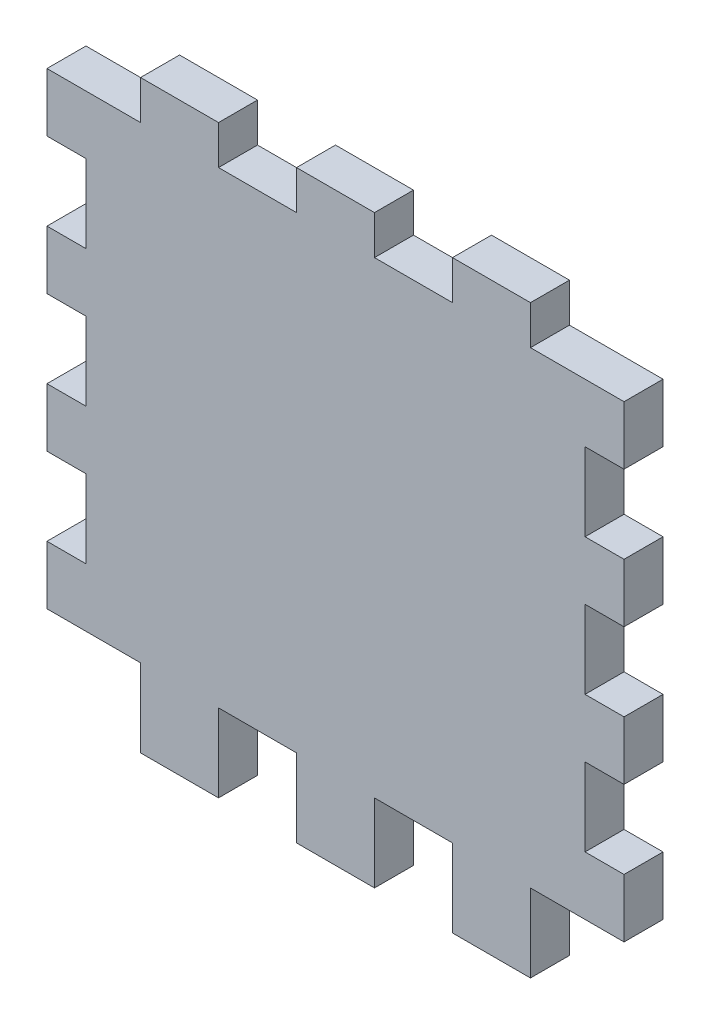
SolidWorks part; units mm, degrees
material "Beech"
ref_plane "Front" through (0, 0, 0) normal (0, 0, 1) x (1, 0, 0)
ref_plane "Top" through (0, 0, 0) normal (0, 1, 0) x (1, 0, 0)
ref_plane "Right" through (0, 0, 0) normal (1, 0, 0) x (0, 0, -1)
sketch "Sketch1" plane through (0, 0, 0) normal (0, 0, 1) x (1, 0, 0)
  line L0 (-2.5, -15) -> (-2.5, -20)
  line L1 (-18.5, -15) -> (18.5, -15)
  line L2 (-18.5, -15) -> (-18.5, 15) construction
  line L3 (-18.5, 15) -> (18.5, 15)
  line L4 (18.5, -15) -> (18.5, 15) construction
  line L5 (-18.5, -15) -> (18.5, 15) construction
  line L6 (-18.5, 15) -> (18.5, -15) construction
  line L7 (7.5, 15) -> (12.5, 15)
  line L8 (7.5, 15) -> (7.5, 17.5)
  line L9 (7.5, 17.5) -> (12.5, 17.5)
  line L10 (12.5, 15) -> (12.5, 17.5)
  line L11 (7.5, 15) -> (12.5, 17.5) construction
  line L12 (7.5, 17.5) -> (12.5, 15) construction
  line L13 (7.5, -15) -> (12.5, -15)
  line L14 (7.5, -15) -> (7.5, -20)
  line L15 (7.5, -20) -> (12.5, -20)
  line L16 (12.5, -15) -> (12.5, -20)
  line L17 (7.5, -15) -> (12.5, -20) construction
  line L18 (7.5, -20) -> (12.5, -15) construction
  line L19 (-2.5, -15) -> (2.5, -15)
  line L20 (2.5, -15) -> (2.5, -20)
  line L21 (-2.5, -20) -> (2.5, -20)
  line L22 (-12.5, -15) -> (-12.5, -20)
  line L23 (-12.5, -15) -> (-7.5, -15)
  line L24 (-7.5, -15) -> (-7.5, -20)
  line L25 (-12.5, -20) -> (-7.5, -20)
  line L30 (-2.5, 15) -> (-2.5, 17.5)
  line L31 (-2.5, 15) -> (2.5, 15)
  line L32 (2.5, 15) -> (2.5, 17.5)
  line L33 (-2.5, 17.5) -> (2.5, 17.5)
  line L34 (-12.5, 15) -> (-12.5, 17.5)
  line L35 (-12.5, 15) -> (-7.5, 15)
  line L36 (-7.5, 15) -> (-7.5, 17.5)
  line L37 (-12.5, 17.5) -> (-7.5, 17.5)
  line L42 (-22.5, 15) -> (-22.5, 17.5) [skipped]
  line L43 (-22.5, 17.5) -> (-17.5, 17.5) [skipped]
  line L44 (-17.5, 15) -> (-17.5, 17.5) [skipped]
  line L45 (-22.5, 15) -> (-17.5, 15) [skipped]
  line L46 (-22.5, -15) -> (-22.5, -20) [skipped]
  line L47 (-22.5, -20) -> (-17.5, -20) [skipped]
  line L48 (-17.5, -15) -> (-17.5, -20) [skipped]
  line L49 (-22.5, -15) -> (-17.5, -15) [skipped]
  line L50 (-18.5, 15) -> (-18.5, 11.25)
  line L51 (-18.5, 11.25) -> (-16, 11.25)
  line L52 (-16, 11.25) -> (-16, 6.25)
  line L53 (-16, 6.25) -> (-18.5, 6.25)
  line L54 (-16, 2.5) -> (-16, -2.5)
  line L55 (-18.5, 2.5) -> (-16, 2.5)
  line L56 (-18.5, 6.25) -> (-18.5, 2.5)
  line L57 (-16, -2.5) -> (-18.5, -2.5)
  line L58 (-16, -6.25) -> (-16, -11.25)
  line L59 (-18.5, -6.25) -> (-16, -6.25)
  line L60 (-18.5, -2.5) -> (-18.5, -6.25)
  line L61 (-16, -11.25) -> (-18.5, -11.25)
  line L62 (-18.5, -11.25) -> (-18.5, -15)
  line L63 (0, 3.4262) -> (0, -2.5) construction
  line L64 (18.5, -11.25) -> (18.5, -15)
  line L65 (16, -11.25) -> (18.5, -11.25)
  line L66 (18.5, -2.5) -> (18.5, -6.25)
  line L67 (18.5, -6.25) -> (16, -6.25)
  line L68 (16, -6.25) -> (16, -11.25)
  line L69 (16, -2.5) -> (18.5, -2.5)
  line L70 (18.5, 6.25) -> (18.5, 2.5)
  line L71 (18.5, 2.5) -> (16, 2.5)
  line L72 (16, 2.5) -> (16, -2.5)
  line L73 (16, 6.25) -> (18.5, 6.25)
  line L74 (16, 11.25) -> (16, 6.25)
  line L75 (18.5, 11.25) -> (16, 11.25)
  line L76 (18.5, 15) -> (18.5, 11.25)
  point P0 (0, 0)
  point P10 (10, 16.25)
  point P16 (10, -17.5)
  dimension "D1" = 30
  dimension "D2" = 37
  dimension "D3" = 6
  dimension "D4" = 5
  dimension "D5" = 5
  dimension "D6" = 6
  dimension "D7" = 5
  dimension "D8" = 2.5
  dimension "D11" = 5
  dimension "D12" = 5
  dimension "D13" = 3.75
  dimension "D14" = 5
  dimension "D15" = 2.5
  dimension "D9" = 4
  dimension "D10" = 4
  dimension "D16" = 3
extrude "Boss-Extrude1" add sketch "Sketch1" along normal blind 2.5
